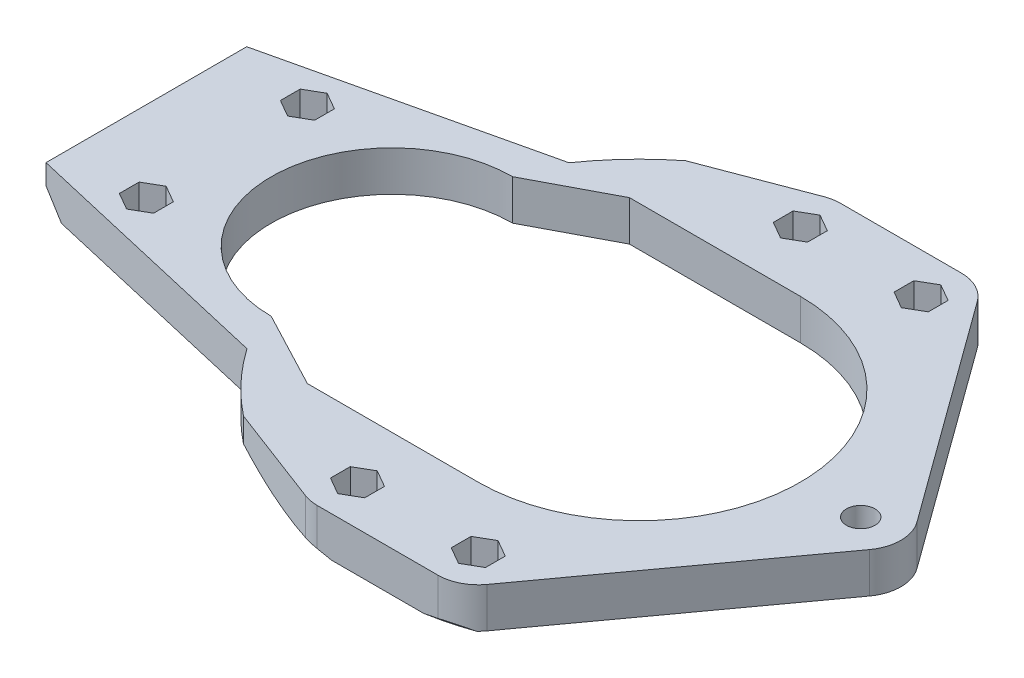
SolidWorks part; units mm, degrees
ref_plane "Front Plane" through (0, 0, 0) normal (0, 0, 1) x (1, 0, 0)
ref_plane "Top Plane" through (0, 0, 0) normal (0, 1, 0) x (1, 0, 0)
ref_plane "Right Plane" through (0, 0, 0) normal (1, 0, 0) x (0, 0, -1)
sketch "Sketch1" plane through (0, 0, 0) normal (0, 1, 0) x (1, 0, 0)
  circle A0 centre (0, 0) radius 70
  dimension "D1" = 140
extrude "Boss-Extrude1" add sketch "Sketch1" along normal blind 10
sketch "Sketch2" plane through (0, 10, 0) normal (0, 1, 0) x (1, 0, 0)
  line L0 (0, 0) -> (-130.144, 0) construction
  line L1 (0, -40) -> (-130.144, -40)
  line L2 (0, 40) -> (-130.144, 40)
  arc A0 (0, -40) -> (0, 40) centre (0, 0) ccw
  arc A1 (-130.144, 40) -> (-130.144, -40) centre (-130.144, 0) ccw
  point P3 (-65.072, 0)
  dimension "D1" = 40
extrude "Cut-Extrude1" cut sketch "Sketch2" against normal through all both and the other way through all
sketch "Sketch3" plane through (0, 0, 0) normal (0, -1, 0) x (-1, 0, 0)
  line L0 (0, 0) -> (59.6125, 0) construction
  circle A0 centre (15, 55) radius 2.75
  circle A1 centre (-15, 55) radius 2.75
  circle A2 centre (-15, -55) radius 2.75
  circle A3 centre (15, -55) radius 2.75
  dimension "D1" = 5.5
extrude "Cut-Extrude2" cut sketch "Sketch3" against normal through all both and the other way through all
sketch "Sketch4" plane through (0, 0, 0) normal (0, -1, 0) x (1, 0, 0)
  line L0 (0, 0) -> (70, 0) construction
  line L1 (-15, -50.0925) -> (-19.25, -52.5463)
  line L2 (-19.25, -52.5463) -> (-19.25, -57.4537)
  line L3 (-19.25, -57.4537) -> (-15, -59.9075)
  line L4 (-15, -59.9075) -> (-10.75, -57.4537)
  line L5 (-10.75, -57.4537) -> (-10.75, -52.5463)
  line L6 (-10.75, -52.5463) -> (-15, -50.0925)
  line L7 (15, -50.0925) -> (10.75, -52.5463)
  line L8 (10.75, -52.5463) -> (10.75, -57.4537)
  line L9 (10.75, -57.4537) -> (15, -59.9075)
  line L10 (15, -59.9075) -> (19.25, -57.4537)
  line L11 (19.25, -57.4537) -> (19.25, -52.5463)
  line L12 (19.25, -52.5463) -> (15, -50.0925)
  line L13 (-15, 59.9075) -> (-19.25, 57.4537)
  line L14 (-19.25, 57.4537) -> (-19.25, 52.5463)
  line L15 (-19.25, 52.5463) -> (-15, 50.0925)
  line L16 (-15, 50.0925) -> (-10.75, 52.5463)
  line L17 (-10.75, 52.5463) -> (-10.75, 57.4537)
  line L18 (-10.75, 57.4537) -> (-15, 59.9075)
  line L19 (15, 59.9075) -> (10.75, 57.4537)
  line L20 (10.75, 57.4537) -> (10.75, 52.5463)
  line L21 (10.75, 52.5463) -> (15, 50.0925)
  line L22 (15, 50.0925) -> (19.25, 52.5463)
  line L23 (19.25, 52.5463) -> (19.25, 57.4537)
  line L24 (19.25, 57.4537) -> (15, 59.9075)
  circle A0 centre (-15, -55) radius 4.25 construction
  circle A1 centre (15, -55) radius 4.25 construction
  circle A2 centre (-15, 55) radius 4.25 construction
  circle A3 centre (15, 55) radius 4.25 construction
  arc A6 (-57.4456, -40) -> (-57.4456, 40) centre (0, 0) ccw construction
  dimension "D1" = 8.5
extrude "Cut-Extrude3" cut sketch "Sketch4" along normal offset from surface (7 mm away) 3 from surface at -10 up to face at (-15, 0, 57.75) starting at face at (-15, 10, 57.75)
sketch "Sketch5" plane through (0, 0, 0) normal (0, -1, 0) x (1, 0, 0)
  line L0 (-57.4456, 40) -> (0, 40) construction
  line L1 (-122.4456, -40) -> (-42.4456, -40)
  line L2 (-122.4456, -40) -> (-122.4456, 40)
  line L3 (-122.4456, 40) -> (-42.4456, 40)
  line L4 (-42.4456, -40) -> (-42.4456, 40)
  line L5 (-122.4456, -40) -> (-42.4456, 40) construction
  line L6 (-122.4456, 40) -> (-42.4456, -40) construction
  point P0 (-82.4456, 0)
  dimension "D1" = 15
  dimension "D2" = 80
extrude "Boss-Extrude2" add sketch "Sketch5" against normal up to surface (10 mm away) up to face at (15, 10, -55)
chamfer "Chamfer1" distance 4 angle 45 1 edges at (70, 0, 0)
sketch "Sketch6" plane through (0, 10, 0) normal (0, 1, 0) x (1, 0, 0)
  line L0 (-122.4456, -40) -> (-122.4456, 40) construction
  line L1 (-102.4456, 24.9075) -> (-106.6956, 22.4537)
  line L2 (-106.6956, 22.4537) -> (-106.6956, 17.5463)
  line L3 (-106.6956, 17.5463) -> (-102.4456, 15.0925)
  line L4 (-102.4456, 15.0925) -> (-98.1956, 17.5463)
  line L5 (-98.1956, 17.5463) -> (-98.1956, 22.4537)
  line L6 (-98.1956, 22.4537) -> (-102.4456, 24.9075)
  line L7 (-102.4456, -15.0925) -> (-106.6956, -17.5463)
  line L8 (-106.6956, -17.5463) -> (-106.6956, -22.4537)
  line L9 (-106.6956, -22.4537) -> (-102.4456, -24.9075)
  line L10 (-102.4456, -24.9075) -> (-98.1956, -22.4537)
  line L11 (-98.1956, -22.4537) -> (-98.1956, -17.5463)
  line L12 (-98.1956, -17.5463) -> (-102.4456, -15.0925)
  line L13 (-122.4456, 40) -> (-57.4456, 40) construction
  circle A0 centre (-102.4456, 20) radius 4.25 construction
  circle A1 centre (-102.4456, -20) radius 4.25 construction
  dimension "D1" = 20
  dimension "D2" = 8.5
  dimension "D3" = 40
  dimension "D4" = 20
extrude "Cut-Extrude4" cut sketch "Sketch6" against normal up to surface (7 mm away) up to face at (-15, 3, 55)
sketch "Sketch7" plane through (0, 3, 0) normal (0, 1, 0) x (1, 0, 0)
  circle A0 centre (-102.4028, 20) radius 2.75
  circle A1 centre (-102.4028, -20) radius 2.75
  dimension "D1" = 5.5
extrude "Cut-Extrude5" cut sketch "Sketch7" against normal through all both and the other way through all
sketch "Sketch8" plane through (0, 10, 0) normal (0, 1, 0) x (1, 0, 0)
  line L0 (-57.4456, -40) -> (-132.9281, -22.5)
  line L1 (-132.9281, -22.5) -> (-132.9281, 22.5)
  line L2 (-132.9281, 22.5) -> (-57.4456, 40)
  line L3 (-122.4456, 40) -> (-57.4456, 40) construction
  line L5 (-57.4456, -40) -> (-122.4456, -40) construction
  line L6 (-57.4456, 40) -> (-157.5677, 66.574)
  line L7 (-157.5677, 66.574) -> (-157.5677, -80.17)
  line L8 (-157.5677, -80.17) -> (-57.4456, -40)
  dimension "D1" = 17.5
  dimension "D2" = 17.5
extrude "Cut-Extrude6" cut sketch "Sketch8" against normal through all both and the other way through all
sketch "Sketch9" plane through (0, 0, 0) normal (0, -1, 0) x (1, 0, 0)
  line L3 (-61.4502, 30) -> (-42.4456, 40)
  line L4 (-42.4456, 40) -> (0, 30)
  line L5 (-61.4502, -30) -> (-42.4456, -40)
  line L6 (-42.4456, -40) -> (0, -30)
  arc A0 (-61.4502, 30) -> (-61.4502, -30) centre (-61.4502, 0) ccw
  arc A1 (0, -30) -> (0, 30) centre (0, 0) ccw
  point P3 (-30.7251, 0)
  dimension "D1" = 30
extrude "Cut-Extrude7" cut sketch "Sketch9" against normal through all both and the other way through all
chamfer "Chamfer3" distance 5 angle 45 1 edges at (-122.4456, 0, 0)
sketch "Sketch10" plane through (0, 0, 0) normal (0, -1, 0) x (1, 0, 0)
  circle A0 centre (55, 0) radius 2.75
  dimension "D1" = 55
  dimension "D2" = 5.5
extrude "Cut-Extrude8" cut sketch "Sketch10" against normal through all both and the other way through all
sketch "Sketch11" plane through (0, 10, 0) normal (0, 1, 0) x (1, 0, 0)
  circle A0 centre (55, 0) radius 3.55
  dimension "D1" = 7.1
extrude "Cut-Extrude9" cut sketch "Sketch11" against normal offset from surface (9 mm away) 9 up to face at (55, 10, -2.75)
sketch "Sketch12" plane through (0, 10, 0) normal (0, 1, 0) x (1, 0, 0)
  line L3 (-122.4456, 24.9303) -> (-18.5473, 64.3497)
  line L4 (-122.4456, -24.9303) -> (-18.5473, -64.3497)
  line L5 (-15, 65) -> (15, 65)
  line L7 (-15, -65) -> (15, -65)
  line L8 (63.0874, 5.8817) -> (23.0874, 60.8817)
  line L9 (63.0874, -5.8817) -> (23.0874, -60.8817)
  line L10 (-122.4456, 24.9303) -> (-122.4456, -24.9303)
  arc A3 (-18.5473, -64.3497) -> (-15, -65) centre (-15, -55) ccw
  arc A4 (15, -65) -> (23.0874, -60.8817) centre (15, -55) ccw
  arc A5 (63.0874, -5.8817) -> (63.0874, 5.8817) centre (55, 0) ccw
  arc A6 (-15, 65) -> (-18.5473, 64.3497) centre (-15, 55) ccw
  arc A7 (23.0874, 60.8817) -> (15, 65) centre (15, 55) ccw
  point P4 (0, 55)
  point P8 (0, 55)
  point P23 (0, -55)
  dimension "D1" = 20
  dimension "D2" = 10
  dimension "D3" = 10
extrude "Cut-Extrude11" cut sketch "Sketch12" against normal through all both and the other way through all flip side to cut
